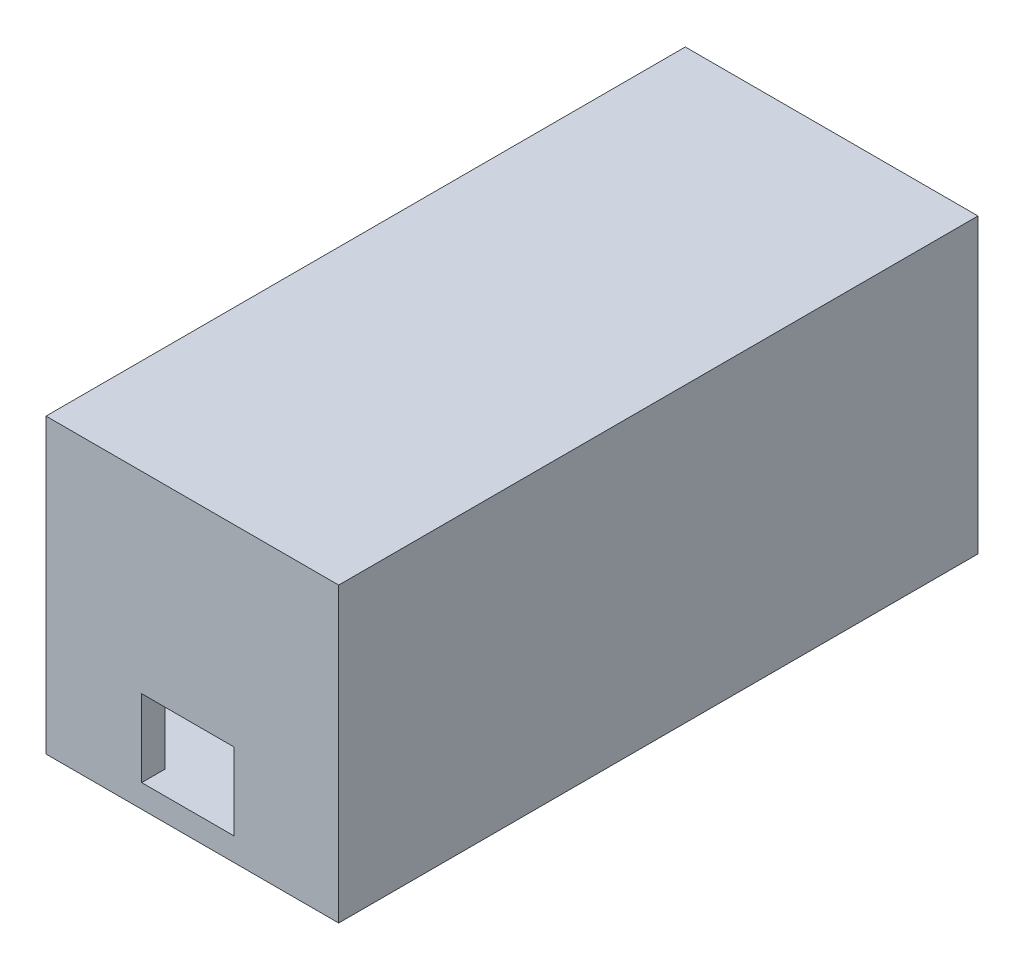
SolidWorks part; units mm, degrees
ref_plane "前视基准面" through (0, 0, 0) normal (0, 0, 1) x (1, 0, 0)
ref_plane "上视基准面" through (0, 0, 0) normal (0, 1, 0) x (1, 0, 0)
ref_plane "右视基准面" through (0, 0, 0) normal (1, 0, 0) x (0, 0, -1)
sketch "草图1" plane through (0, 0, 0) normal (0, 0, 1) x (1, 0, 0)
  line L0 (1.5, 17.5) -> (17.5, 17.5)
  line L1 (0, 0) -> (19, 0)
  line L2 (0, 0) -> (0, 19)
  line L3 (0, 19) -> (19, 19)
  line L4 (19, 0) -> (19, 19)
  line L5 (17.5, 1.5) -> (17.5, 17.5)
  line L6 (1.5, 1.5) -> (17.5, 1.5)
  line L7 (1.5, 1.5) -> (1.5, 17.5)
  dimension "D1" = 19
  dimension "D2" = 19
  dimension "D3" = 1.5
extrude "凸台-拉伸1" add sketch "草图1" along normal blind 40
sketch "草图2" plane through (0, 0, 40) normal (0, 0, 1) x (1, 0, 0)
  line L0 (19, 0) -> (19, 19) construction
  line L1 (0, 19) -> (19, 19)
  line L2 (0, 19) -> (0, 0)
  line L3 (0, 0) -> (19, 0)
  line L4 (19, 19) -> (19, 0)
  line L5 (0, 0) -> (19, 0) construction
  line L6 (1.5, 1.5) -> (17.5, 1.5) construction
  line L7 (6.211, 6.5) -> (12.211, 6.5)
  line L8 (6.211, 6.5) -> (6.211, 1.5)
  line L9 (6.211, 1.5) -> (12.211, 1.5)
  line L10 (12.211, 6.5) -> (12.211, 1.5)
  dimension "D1" = 6
  dimension "D2" = 5
extrude "凸台-拉伸2" add sketch "草图2" along normal blind 1.5
